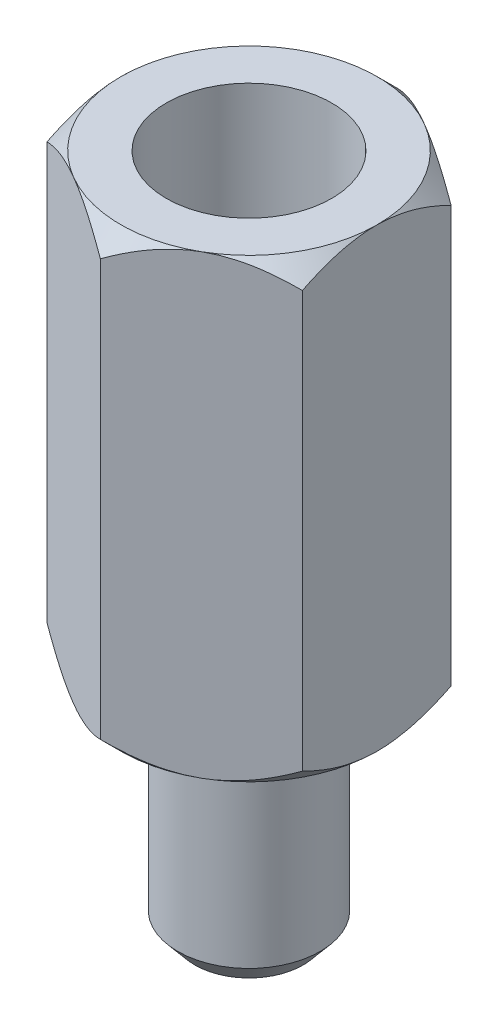
SolidWorks part; units mm, degrees
ref_plane "Front Plane" through (0, 0, 0) normal (0, 0, 1) x (1, 0, 0)
ref_plane "Top Plane" through (0, 0, 0) normal (0, 1, 0) x (1, 0, 0)
ref_plane "Right Plane" through (0, 0, 0) normal (1, 0, 0) x (0, 0, -1)
sketch "Sketch1" plane through (0, 0, 0) normal (0, 1, 0) x (1, 0, 0)
  circle A0 centre (0, 0) radius 1.25
  dimension "D1" = 2.5
extrude "Boss-Extrude1" add sketch "Sketch1" along normal blind 3.9
sketch "Sketch2" plane through (0, 3.9, 0) normal (0, 1, 0) x (1, 0, 0)
  line L1 (2.2449, -1.3078) -> (2.2551, 1.2902)
  line L2 (2.2551, 1.2902) -> (0.0102, 2.5981)
  line L3 (0.0102, 2.5981) -> (-2.2449, 1.3078)
  line L4 (-2.2449, 1.3078) -> (-2.2551, -1.2902)
  line L5 (-2.2551, -1.2902) -> (-0.0102, -2.5981)
  line L6 (-0.0102, -2.5981) -> (2.2449, -1.3078)
  circle A0 centre (0, 0) radius 2.25 construction
  point P1 (0, 0)
  dimension "D1" = 4.5
extrude "Boss-Extrude2" add sketch "Sketch2" along normal blind 8
sketch "Sketch3" plane through (0, 11.9, 0) normal (0, 1, 0) x (1, 0, 0)
  circle A0 centre (0, 0) radius 1.4518
extrude "Cut-Extrude1" cut sketch "Sketch3" against normal blind 4.8
sketch "Sketch4" plane through (0, 11.9, 0) normal (0, 1, 0) x (1, 0, 0)
  circle A0 centre (0, 0) radius 2.25
extrude "Cut-Extrude2" cut sketch "Sketch4" against normal through all draft 45 flip side to cut
sketch "Sketch5" plane through (0, 3.9, 0) normal (0, -1, 0) x (1, 0, 0)
  circle A0 centre (0, 0) radius 2.25
extrude "Cut-Extrude3" cut sketch "Sketch5" against normal through all draft 45 flip side to cut
chamfer "Chamfer1" distance 0.3 angle 50 1 edges at (0, 0, 1.25)
